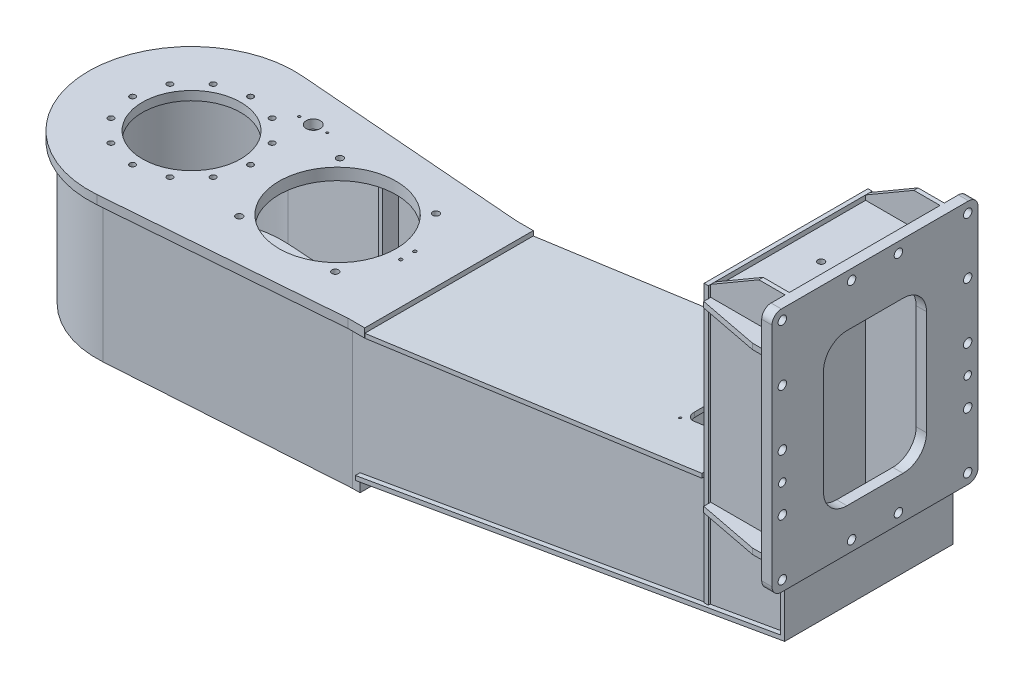
SolidWorks part; units mm, degrees
ref_plane "正面" through (0, 0, 0) normal (0, 0, 1) x (1, 0, 0)
ref_plane "平面" through (0, 0, 0) normal (0, 1, 0) x (1, 0, 0)
ref_plane "右側面" through (0, 0, 0) normal (1, 0, 0) x (0, 0, -1)
sketch "ｽｹｯﾁ1" plane through (0, 0, 0) normal (0, 1, 0) x (1, 0, 0)
  circle A0 centre (0, 0) radius 203
  circle A1 centre (0, 0) radius 194
extrude "ﾎﾞｽ - 押し出し1" add sketch "ｽｹｯﾁ1" against normal blind 301
sketch "ｽｹｯﾁ2" plane through (0, 0, 0) normal (0, 1, 0) x (1, 0, 0)
  line L0 (0, 0) -> (16.2249, -249.4729)
  line L1 (16.2249, -249.4729) -> (300, -249.4729)
  line L2 (300, -249.4729) -> (300, 249.4729)
  line L3 (300, 249.4729) -> (16.2249, 249.4729)
  line L4 (16.2249, 249.4729) -> (0, 0)
extrude "ｶｯﾄ - 押し出し1" cut sketch "ｽｹｯﾁ2" against normal through all and the other way through all
ref_plane "平面1" through (0, -301, 0) normal (0, 1, 0) x (1, 0, 0)
sketch "ｽｹｯﾁ4" plane through (0, -301, 0) normal (0, 1, 0) x (1, 0, 0)
  circle A0 centre (0, 0) radius 194
extrude "ﾎﾞｽ - 押し出し2" add sketch "ｽｹｯﾁ4" along normal blind 20
sketch "ｽｹｯﾁ5" plane through (0, -301, 0) normal (0, 1, 0) x (1, 0, 0)
  line L0 (12.5905, -193.591) -> (513.7, -161)
  line L1 (513.7, -161) -> (518, -161)
  line L2 (518, -161) -> (518, 161)
  line L3 (518, 161) -> (513.7, 161)
  line L4 (513.7, 161) -> (12.5905, 193.591)
  line L5 (12.5905, 193.591) -> (12.5905, -193.591)
extrude "ﾎﾞｽ - 押し出し3" add sketch "ｽｹｯﾁ5" along normal blind 20
sketch "ｽｹｯﾁ6" plane through (0, -301, 0) normal (0, 1, 0) x (1, 0, 0)
  circle A0 centre (0, 0) radius 159
sketch "ｽｹｯﾁ7" plane through (0, -301, 0) normal (0, 1, 0) x (1, 0, 0)
  circle A0 centre (0, 0) radius 159
extrude "ｶｯﾄ - 押し出し3" cut sketch "ｽｹｯﾁ7" along normal blind 20
sketch "ｽｹｯﾁ8" plane through (0, -301, 0) normal (0, 1, 0) x (1, 0, 0)
  line L0 (10.319, -158.6648) -> (468.0175, -128.8976)
  line L1 (468.0175, -128.8976) -> (468.0175, 128.8976)
  line L2 (468.0175, 128.8976) -> (10.319, 158.6648)
  line L3 (10.319, 158.6648) -> (10.319, -158.6648)
sketch "ｽｹｯﾁ9" plane through (0, -301, 0) normal (0, 1, 0) x (1, 0, 0)
  line L0 (10.319, -158.6648) -> (468.0175, -128.8976)
  line L1 (468.0175, -128.8976) -> (468.0175, 128.8976)
  line L2 (468.0175, 128.8976) -> (10.319, 158.6648)
  line L3 (10.319, 158.6648) -> (10.319, -158.6648)
extrude "ｶｯﾄ - 押し出し5" cut sketch "ｽｹｯﾁ9" along normal blind 20
fillet "ﾌｨﾚｯﾄ1" radius 25 2 edges at (468.0175, -291, -128.8976) (468.0175, -291, 128.8976)
sketch "ｽｹｯﾁ10" plane through (0, 0, 0) normal (0, 1, 0) x (1, 0, 0)
  line L0 (12.5905, 193.591) -> (513.7, 161)
  line L1 (513.7, 161) -> (530, 161)
  line L2 (530, 161) -> (530, 170)
  line L3 (530, 170) -> (514, 170)
  line L4 (514, 170) -> (13.1746, 202.572)
  line L5 (13.1746, 202.572) -> (12.5905, 193.591)
  line L6 (12.5905, -193.591) -> (513.7, -161)
  line L7 (513.7, -161) -> (530, -161)
  line L8 (530, -161) -> (530, -170)
  line L9 (530, -170) -> (514, -170)
  line L10 (514, -170) -> (13.1746, -202.572)
  line L11 (13.1746, -202.572) -> (12.5905, -193.591)
extrude "ﾎﾞｽ - 押し出し4" add sketch "ｽｹｯﾁ10" against normal blind 301
sketch "ｽｹｯﾁ11" plane through (0, 0, 0) normal (0, 1, 0) x (1, 0, 0)
  circle A0 centre (0, 0) radius 220
extrude "ﾎﾞｽ - 押し出し5" add sketch "ｽｹｯﾁ11" along normal blind 19
sketch "ｽｹｯﾁ12" plane through (0, 0, 0) normal (0, 1, 0) x (1, 0, 0)
  line L0 (17.3506, -219.3147) -> (514.3, -180)
  line L1 (514.3, -180) -> (550, -180)
  line L2 (550, -180) -> (550, 180)
  line L3 (550, 180) -> (514.3, 180)
  line L4 (514.3, 180) -> (17.3506, 219.3147)
  line L5 (17.3506, 219.3147) -> (17.3506, -219.3147)
extrude "ﾎﾞｽ - 押し出し6" add sketch "ｽｹｯﾁ12" along normal blind 19
sketch "ｽｹｯﾁ13" plane through (0, 0, 0) normal (0, 1, 0) x (1, 0, 0)
  line L0 (175, 135) -> (475, 135)
  line L1 (475, 135) -> (475, -135)
  line L2 (475, -135) -> (175, -135)
  line L3 (175, -135) -> (175, 135)
extrude "ﾎﾞｽ - 押し出し7" add sketch "ｽｹｯﾁ13" against normal blind 6
ref_plane "平面2" through (518, 0, 0) normal (1, 0, 0) x (0, 0, -1)
sketch "ｽｹｯﾁ15" plane through (518, 0, 0) normal (1, 0, 0) x (0, 0, -1)
  line L0 (161, -301) -> (-161, -301)
  line L1 (-161, -301) -> (-161, -7)
  line L2 (-161, -7) -> (-151, 3)
  line L3 (-151, 3) -> (151, 3)
  line L4 (151, 3) -> (161, -7)
  line L5 (161, -7) -> (161, -301)
extrude "ﾎﾞｽ - 押し出し8" add sketch "ｽｹｯﾁ15" along normal blind 12
sketch "ｽｹｯﾁ16" plane through (518, 0, 0) normal (1, 0, 0) x (0, 0, -1)
  line L0 (-111, -220) -> (-111, -97)
  line L1 (-81, -67) -> (81, -67)
  line L2 (111, -97) -> (111, -220)
  line L3 (81, -250) -> (-81, -250)
  arc A0 (-111, -97) -> (-81, -67) centre (-81, -97) cw
  arc A1 (81, -67) -> (111, -97) centre (81, -97) cw
  arc A2 (111, -220) -> (81, -250) centre (81, -220) cw
  arc A3 (-81, -250) -> (-111, -220) centre (-81, -220) cw
sketch "ｽｹｯﾁ17" plane through (518, 0, 0) normal (1, 0, 0) x (0, 0, -1)
  line L0 (-111, -220) -> (-111, -97)
  line L1 (-81, -67) -> (81, -67)
  line L2 (111, -97) -> (111, -220)
  line L3 (81, -250) -> (-81, -250)
  arc A0 (-111, -97) -> (-81, -67) centre (-81, -97) cw
  arc A1 (81, -67) -> (111, -97) centre (81, -97) cw
  arc A2 (111, -220) -> (81, -250) centre (81, -220) cw
  arc A3 (-81, -250) -> (-111, -220) centre (-81, -220) cw
extrude "ｶｯﾄ - 押し出し7" cut sketch "ｽｹｯﾁ17" along normal blind 12
ref_plane "平面3" through (0, 0, 161) normal (0, 0, 1) x (1, 0, 0)
ref_plane "平面4" through (0, 0, -161) normal (0, 0, 1) x (1, 0, 0)
sketch "ｽｹｯﾁ20" plane through (0, 0, 161) normal (0, 0, 1) x (1, 0, 0)
  line L0 (530, -273.1369) -> (1270, -143.5554)
  line L1 (1270, -143.5554) -> (1270, 109.9881)
  line L2 (1270, 109.9881) -> (530, 6.2151)
  line L3 (530, 6.2151) -> (530, -273.1369)
extrude "ﾎﾞｽ - 押し出し9" add sketch "ｽｹｯﾁ20" along normal blind 9
sketch "ｽｹｯﾁ21" plane through (0, 0, -161) normal (0, 0, 1) x (1, 0, 0)
  line L0 (530, -273.1369) -> (1270, -143.5554)
  line L1 (1270, -143.5554) -> (1270, 109.9881)
  line L2 (1270, 109.9881) -> (530, 6.2151)
  line L3 (530, 6.2151) -> (530, -273.1369)
extrude "ﾎﾞｽ - 押し出し10" add sketch "ｽｹｯﾁ21" against normal blind 9
sketch "ｽｹｯﾁ22" plane through (0, 0, 0) normal (0, 0, 1) x (1, 0, 0)
  line L0 (551.2, 0.1) -> (1270, 100.9)
  line L1 (1270, 100.9) -> (1270, 109.9881)
  line L2 (1270, 109.9881) -> (549.9501, 9.0128)
  line L3 (549.9501, 9.0128) -> (551.2, 0.1)
extrude "ﾎﾞｽ - 押し出し11" add sketch "ｽｹｯﾁ22" against normal blind 180 and the other way blind 180
sketch "ｽｹｯﾁ23" plane through (0, 0, 0) normal (0, 0, 1) x (1, 0, 0)
  line L0 (530, -264) -> (1438, -105)
  line L1 (1438, -105) -> (1438, -5)
  line L2 (1438, -5) -> (1447, -5)
  line L3 (1447, -5) -> (1447, -112.561)
  line L4 (1447, -112.561) -> (530, -273.1369)
  line L5 (530, -273.1369) -> (530, -264)
extrude "ﾎﾞｽ - 押し出し12" add sketch "ｽｹｯﾁ23" against normal blind 180 and the other way blind 180
sketch "ｽｹｯﾁ24" plane through (0, 0, 0) normal (0, 0, 1) x (1, 0, 0)
  line L0 (909.0501, 59.3707) -> (917.9629, 60.6206)
  line L1 (917.9629, 60.6206) -> (954.3466, -198.8296)
  line L2 (954.3466, -198.8296) -> (945.4763, -200.3828)
  line L3 (945.4763, -200.3828) -> (909.0501, 59.3707)
extrude "ﾎﾞｽ - 押し出し13" add sketch "ｽｹｯﾁ24" against normal blind 161 and the other way blind 161
ref_plane "平面5" through (0, 0, 161) normal (0, 0, 1) x (1, 0, 0)
ref_plane "平面6" through (0, 0, -161) normal (0, 0, 1) x (1, 0, 0)
sketch "ｽｹｯﾁ29" plane through (908.596, 127.4158, 0) normal (0.9903, 0.1389, 0) x (0, 0, -1)
  line L0 (81, -270.0172) -> (-81, -270.0172)
  line L1 (-111, -240.0172) -> (-111, -157.0172)
  line L2 (-81, -127.0172) -> (81, -127.0172)
  line L3 (111, -157.0172) -> (111, -240.0172)
  arc A0 (-81, -270.0172) -> (-111, -240.0172) centre (-81, -240.0172) cw
  arc A1 (-111, -157.0172) -> (-81, -127.0172) centre (-81, -157.0172) cw
  arc A2 (81, -127.0172) -> (111, -157.0172) centre (81, -157.0172) cw
  arc A3 (111, -240.0172) -> (81, -270.0172) centre (81, -240.0172) cw
extrude "ｶｯﾄ - 押し出し8" cut sketch "ｽｹｯﾁ29" against normal blind 9
ref_plane "平面7" through (1270, 0, 0) normal (1, 0, 0) x (0, 0, -1)
sketch "ｽｹｯﾁ31" plane through (1270, 0, 0) normal (1, 0, 0) x (0, 0, -1)
  line L0 (175, -132) -> (-175, -132)
  line L1 (-175, -132) -> (-175, 459)
  line L2 (-175, 459) -> (175, 459)
  line L3 (175, 459) -> (175, -132)
extrude "ﾎﾞｽ - 押し出し14" add sketch "ｽｹｯﾁ31" along normal blind 9
sketch "ｽｹｯﾁ32" plane through (0, 0, 161) normal (0, 0, 1) x (1, 0, 0)
  line L0 (1279, -5) -> (1438, -5)
  line L1 (1438, -5) -> (1438, 519)
  line L2 (1438, 519) -> (1382, 519)
  line L3 (1382, 519) -> (1279, 459)
  line L4 (1279, 459) -> (1279, -5)
ref_plane "平面8" through (0, 0, 161) normal (0, 0, 1) x (1, 0, 0)
ref_plane "平面9" through (0, 0, -161) normal (0, 0, 1) x (1, 0, 0)
ref_plane "平面10" through (1270, 0, 0) normal (1, 0, 0) x (0, 0, -1)
sketch "ｽｹｯﾁ36" plane through (0, 0, 161) normal (0, 0, 1) x (1, 0, 0)
  line L0 (1279, -5) -> (1460, -5)
  line L1 (1460, -5) -> (1460, 519)
  line L2 (1460, 519) -> (1382, 519)
  line L3 (1382, 519) -> (1279, 459)
  line L4 (1279, 459) -> (1279, -5)
extrude "ﾎﾞｽ - 押し出し16" add sketch "ｽｹｯﾁ36" along normal blind 9
sketch "ｽｹｯﾁ37" plane through (0, 0, -161) normal (0, 0, 1) x (1, 0, 0)
  line L0 (1279, -5) -> (1460, -5)
  line L1 (1460, -5) -> (1460, 519)
  line L2 (1460, 519) -> (1382, 519)
  line L3 (1382, 519) -> (1279, 459)
  line L4 (1279, 459) -> (1279, -5)
extrude "ﾎﾞｽ - 押し出し17" add sketch "ｽｹｯﾁ37" against normal blind 9
ref_plane "平面11" through (0, 44, 0) normal (0, 1, 0) x (1, 0, 0)
sketch "ｽｹｯﾁ39" plane through (0, 44, 0) normal (0, 1, 0) x (1, 0, 0)
  line L0 (1279, 170) -> (1431, 170)
  line L1 (1431, 170) -> (1438, 177)
  line L2 (1438, 177) -> (1438, 203)
  line L3 (1438, 203) -> (1431, 210)
  line L4 (1431, 210) -> (1408, 210)
  line L5 (1408, 210) -> (1279, 185)
  line L6 (1279, 185) -> (1279, 170)
  line L7 (1279, -170) -> (1431, -170)
  line L8 (1431, -170) -> (1438, -177)
  line L9 (1438, -177) -> (1438, -203)
  line L10 (1438, -203) -> (1431, -210)
  line L11 (1431, -210) -> (1408, -210)
  line L12 (1408, -210) -> (1279, -185)
  line L13 (1279, -185) -> (1279, -170)
extrude "ﾎﾞｽ - 押し出し18" add sketch "ｽｹｯﾁ39" along normal blind 12
ref_plane "平面12" through (0, 423, 0) normal (0, 1, 0) x (1, 0, 0)
sketch "ｽｹｯﾁ41" plane through (0, 423, 0) normal (0, 1, 0) x (1, 0, 0)
  line L0 (1279, 170) -> (1431, 170)
  line L1 (1431, 170) -> (1438, 177)
  line L2 (1438, 177) -> (1438, 203)
  line L3 (1438, 203) -> (1431, 210)
  line L4 (1431, 210) -> (1408, 210)
  line L5 (1408, 210) -> (1279, 185)
  line L6 (1279, 185) -> (1279, 170)
  line L7 (1279, -170) -> (1431, -170)
  line L8 (1431, -170) -> (1438, -177)
  line L9 (1438, -177) -> (1438, -203)
  line L10 (1438, -203) -> (1431, -210)
  line L11 (1431, -210) -> (1408, -210)
  line L12 (1408, -210) -> (1279, -185)
  line L13 (1279, -185) -> (1279, -170)
extrude "ﾎﾞｽ - 押し出し19" add sketch "ｽｹｯﾁ41" along normal blind 12
ref_plane "平面13" through (0, 437, 0) normal (0, 1, 0) x (1, 0, 0)
sketch "ｽｹｯﾁ43" plane through (0, 437, 0) normal (0, 1, 0) x (1, 0, 0)
  line L0 (1279, 161) -> (1438, 161)
  line L1 (1438, 161) -> (1438, -161)
  line L2 (1438, -161) -> (1279, -161)
  line L3 (1279, -161) -> (1279, 161)
extrude "ﾎﾞｽ - 押し出し20" add sketch "ｽｹｯﾁ43" along normal blind 12
ref_plane "平面14" through (1438, 0, 0) normal (1, 0, 0) x (0, 0, -1)
sketch "ｽｹｯﾁ45" plane through (1438, 0, 0) normal (1, 0, 0) x (0, 0, -1)
  line L0 (-220, 15) -> (-220, 499)
  line L1 (-200, 519) -> (200, 519)
  line L2 (220, 499) -> (220, 15)
  line L3 (200, -5) -> (-200, -5)
  arc A0 (-220, 499) -> (-200, 519) centre (-200, 499) cw
  arc A1 (200, 519) -> (220, 499) centre (200, 499) cw
  arc A2 (220, 15) -> (200, -5) centre (200, 15) cw
  arc A3 (-200, -5) -> (-220, 15) centre (-200, 15) cw
extrude "ﾎﾞｽ - 押し出し21" add sketch "ｽｹｯﾁ45" along normal blind 22
sketch "ｽｹｯﾁ46" plane through (1438, 0, 0) normal (1, 0, 0) x (0, 0, -1)
  line L0 (-110, 135) -> (-110, 359)
  line L1 (-60, 409) -> (60, 409)
  line L2 (110, 359) -> (110, 135)
  line L3 (60, 85) -> (-60, 85)
  arc A0 (-110, 359) -> (-60, 409) centre (-60, 359) cw
  arc A1 (60, 409) -> (110, 359) centre (60, 359) cw
  arc A2 (110, 135) -> (60, 85) centre (60, 135) cw
  arc A3 (-60, 85) -> (-110, 135) centre (-60, 135) cw
sketch "ｽｹｯﾁ47" plane through (1438, 0, 0) normal (1, 0, 0) x (0, 0, -1)
  line L0 (-110, 135) -> (-110, 359)
  line L1 (-60, 409) -> (60, 409)
  line L2 (110, 359) -> (110, 135)
  line L3 (60, 85) -> (-60, 85)
  arc A0 (-110, 359) -> (-60, 409) centre (-60, 359) cw
  arc A1 (60, 409) -> (110, 359) centre (60, 359) cw
  arc A2 (110, 135) -> (60, 85) centre (60, 135) cw
  arc A3 (-60, 85) -> (-110, 135) centre (-60, 135) cw
extrude "ｶｯﾄ - 押し出し10" cut sketch "ｽｹｯﾁ47" along normal blind 22
sketch "ｽｹｯﾁ48" plane through (0, 0, 0) normal (0, 1, 0) x (1, 0, 0)
  line L0 (253.6175, 145.9656) -> (262.6175, 145.3656)
  line L1 (262.6175, 145.3656) -> (264.7175, 177.1935)
  line L2 (264.7175, 177.1935) -> (255.7175, 177.7788)
  line L3 (255.7175, 177.7788) -> (253.6175, 145.9656)
  line L4 (253.6175, -145.9656) -> (262.6175, -145.3656)
  line L5 (262.6175, -145.3656) -> (264.7175, -177.1935)
  line L6 (264.7175, -177.1935) -> (255.7175, -177.7788)
  line L7 (255.7175, -177.7788) -> (253.6175, -145.9656)
extrude "ﾎﾞｽ - 押し出し22" add sketch "ｽｹｯﾁ48" against normal blind 301
sketch "ｽｹｯﾁ49" plane through (0, 0, 0) normal (0, 1, 0) x (1, 0, 0)
  circle A0 centre (0, 0) radius 105
sketch "ｽｹｯﾁ50" plane through (0, 0, 0) normal (0, 1, 0) x (1, 0, 0)
  circle A0 centre (0, 0) radius 105
extrude "ｶｯﾄ - 押し出し12" cut sketch "ｽｹｯﾁ50" along normal blind 19
sketch "ｽｹｯﾁ51" plane through (0, 0, 0) normal (0, 1, 0) x (1, 0, 0)
  circle A0 centre (126, 0) radius 6
  circle A1 centre (109.1192, -63) radius 6
  circle A2 centre (63, -109.1192) radius 6
  circle A3 centre (0, -126) radius 6
  circle A4 centre (-63, -109.1192) radius 6
  circle A5 centre (-109.1192, -63) radius 6
  circle A6 centre (-126, 0) radius 6
  circle A7 centre (-109.1192, 63) radius 6
  circle A8 centre (-63, 109.1192) radius 6
  circle A9 centre (0, 126) radius 6
  circle A10 centre (63, 109.1192) radius 6
  circle A11 centre (109.1192, 63) radius 6
sketch "ｽｹｯﾁ52" plane through (0, 0, 0) normal (0, 1, 0) x (1, 0, 0)
  circle A0 centre (126, 0) radius 6
  circle A1 centre (109.1192, -63) radius 6
  circle A2 centre (63, -109.1192) radius 6
  circle A3 centre (0, -126) radius 6
  circle A4 centre (-63, -109.1192) radius 6
  circle A5 centre (-109.1192, -63) radius 6
  circle A6 centre (-126, 0) radius 6
  circle A7 centre (-109.1192, 63) radius 6
  circle A8 centre (-63, 109.1192) radius 6
  circle A9 centre (0, 126) radius 6
  circle A10 centre (63, 109.1192) radius 6
  circle A11 centre (109.1192, 63) radius 6
extrude "ｶｯﾄ - 押し出し14" cut sketch "ｽｹｯﾁ52" along normal blind 19
sketch "ｽｹｯﾁ53" plane through (0, 0, 0) normal (0, 1, 0) x (1, 0, 0)
  circle A0 centre (119, 141) radius 15
sketch "ｽｹｯﾁ54" plane through (0, 0, 0) normal (0, 1, 0) x (1, 0, 0)
  circle A0 centre (119, 141) radius 15
extrude "ｶｯﾄ - 押し出し16" cut sketch "ｽｹｯﾁ54" along normal blind 19
sketch "ｽｹｯﾁ55" plane through (0, 0, 0) normal (0, 1, 0) x (1, 0, 0)
  circle A0 centre (89, 141) radius 2.5
  circle A1 centre (149, 141) radius 2.5
sketch "ｽｹｯﾁ56" plane through (0, 0, 0) normal (0, 1, 0) x (1, 0, 0)
  circle A0 centre (89, 141) radius 2.5
  circle A1 centre (149, 141) radius 2.5
extrude "ｶｯﾄ - 押し出し18" cut sketch "ｽｹｯﾁ56" along normal blind 19
ref_plane "平面15" through (0, -6, 0) normal (0, 1, 0) x (1, 0, 0)
sketch "ｽｹｯﾁ58" plane through (0, -6, 0) normal (0, 1, 0) x (1, 0, 0)
  circle A0 centre (312, 0) radius 125
sketch "ｽｹｯﾁ59" plane through (0, -6, 0) normal (0, 1, 0) x (1, 0, 0)
  circle A0 centre (312, 0) radius 125
extrude "ｶｯﾄ - 押し出し20" cut sketch "ｽｹｯﾁ59" along normal blind 25
sketch "ｽｹｯﾁ60" plane through (0, -6, 0) normal (0, 1, 0) x (1, 0, 0)
  circle A0 centre (209.5, 107.5) radius 7
  circle A1 centre (209.5, -107.5) radius 7
  circle A2 centre (414.5, 107.5) radius 7
  circle A3 centre (414.5, -107.5) radius 7
sketch "ｽｹｯﾁ61" plane through (0, -6, 0) normal (0, 1, 0) x (1, 0, 0)
  circle A0 centre (209.5, 107.5) radius 7
  circle A1 centre (209.5, -107.5) radius 7
  circle A2 centre (414.5, 107.5) radius 7
  circle A3 centre (414.5, -107.5) radius 7
extrude "ｶｯﾄ - 押し出し22" cut sketch "ｽｹｯﾁ61" along normal blind 25
sketch "ｽｹｯﾁ62" plane through (0, -6, 0) normal (0, 1, 0) x (1, 0, 0)
  circle A0 centre (462, 15) radius 3.4
  circle A1 centre (462, -15) radius 3.4
sketch "ｽｹｯﾁ63" plane through (0, -6, 0) normal (0, 1, 0) x (1, 0, 0)
  circle A0 centre (462, 15) radius 3.4
  circle A1 centre (462, -15) radius 3.4
extrude "ｶｯﾄ - 押し出し24" cut sketch "ｽｹｯﾁ63" along normal blind 25
sketch "ｽｹｯﾁ64" plane through (9.3669, -66.7952, 0) normal (-0.1389, 0.9903, 0) x (0.9903, 0.1389, 0)
  line L0 (1205.5769, 55) -> (1205.5769, -55)
  line L1 (1185.5769, -75) -> (1150.5769, -75)
  line L2 (1130.5769, -55) -> (1130.5769, 55)
  line L3 (1150.5769, 75) -> (1185.5769, 75)
  arc A0 (1205.5769, -55) -> (1185.5769, -75) centre (1185.5769, -55) cw
  arc A1 (1150.5769, -75) -> (1130.5769, -55) centre (1150.5769, -55) cw
  arc A2 (1130.5769, 55) -> (1150.5769, 75) centre (1150.5769, 55) cw
  arc A3 (1185.5769, 75) -> (1205.5769, 55) centre (1185.5769, 55) cw
extrude "ｶｯﾄ - 押し出し25" cut sketch "ｽｹｯﾁ64" against normal blind 9
sketch "ｽｹｯﾁ65" plane through (9.3669, -66.7952, 0) normal (-0.1389, 0.9903, 0) x (0.9903, 0.1389, 0)
  circle A0 centre (1125.5769, 80) radius 2.5
  circle A1 centre (1125.5769, -80) radius 2.5
  circle A2 centre (1210.5769, 80) radius 2.5
  circle A3 centre (1210.5769, -80) radius 2.5
extrude "ｶｯﾄ - 押し出し26" cut sketch "ｽｹｯﾁ65" against normal blind 9
sketch "ｽｹｯﾁ66" plane through (1270, 0, 0) normal (1, 0, 0) x (0, 0, -1)
  circle A0 centre (0, 319) radius 65
sketch "ｽｹｯﾁ67" plane through (1270, 0, 0) normal (1, 0, 0) x (0, 0, -1)
  circle A0 centre (0, 319) radius 65
extrude "ｶｯﾄ - 押し出し28" cut sketch "ｽｹｯﾁ67" along normal blind 9
sketch "ｽｹｯﾁ68" plane through (1270, 0, 0) normal (1, 0, 0) x (0, 0, -1)
  circle A0 centre (-53.033, 372.033) radius 2.5
  circle A1 centre (53.033, 372.033) radius 2.5
  circle A2 centre (53.033, 265.967) radius 2.5
  circle A3 centre (-53.033, 265.967) radius 2.5
sketch "ｽｹｯﾁ69" plane through (1270, 0, 0) normal (1, 0, 0) x (0, 0, -1)
  circle A0 centre (-53.033, 372.033) radius 2.5
  circle A1 centre (53.033, 372.033) radius 2.5
  circle A2 centre (53.033, 265.967) radius 2.5
  circle A3 centre (-53.033, 265.967) radius 2.5
extrude "ｶｯﾄ - 押し出し30" cut sketch "ｽｹｯﾁ69" along normal blind 9
sketch "ｽｹｯﾁ70" plane through (0, 437, 0) normal (0, 1, 0) x (1, 0, 0)
  circle A0 centre (1345, 0) radius 7
sketch "ｽｹｯﾁ71" plane through (0, 437, 0) normal (0, 1, 0) x (1, 0, 0)
  circle A0 centre (1345, 0) radius 7
extrude "ｶｯﾄ - 押し出し32" cut sketch "ｽｹｯﾁ71" along normal blind 12
sketch "ｽｹｯﾁ72" plane through (1438, 0, 0) normal (1, 0, 0) x (0, 0, -1)
  circle A0 centre (198, 17) radius 9
  circle A1 centre (198, 137) radius 9
  circle A2 centre (198, 257) radius 9
  circle A3 centre (198, 377) radius 9
  circle A4 centre (198, 497) radius 9
  circle A5 centre (-198, 17) radius 9
  circle A6 centre (-198, 137) radius 9
  circle A7 centre (-198, 257) radius 9
  circle A8 centre (-198, 377) radius 9
  circle A9 centre (-198, 497) radius 9
  circle A10 centre (50, 17) radius 9
  circle A11 centre (50, 497) radius 9
  circle A12 centre (-50, 17) radius 9
  circle A13 centre (-50, 497) radius 9
sketch "ｽｹｯﾁ73" plane through (1438, 0, 0) normal (1, 0, 0) x (0, 0, -1)
  circle A0 centre (198, 17) radius 9
  circle A1 centre (198, 137) radius 9
  circle A2 centre (198, 257) radius 9
  circle A3 centre (198, 377) radius 9
  circle A4 centre (198, 497) radius 9
  circle A5 centre (-198, 17) radius 9
  circle A6 centre (-198, 137) radius 9
  circle A7 centre (-198, 257) radius 9
  circle A8 centre (-198, 377) radius 9
  circle A9 centre (-198, 497) radius 9
  circle A10 centre (50, 17) radius 9
  circle A11 centre (50, 497) radius 9
  circle A12 centre (-50, 17) radius 9
  circle A13 centre (-50, 497) radius 9
extrude "ｶｯﾄ - 押し出し34" cut sketch "ｽｹｯﾁ73" along normal blind 22
sketch "ｽｹｯﾁ74" plane through (1438, 0, 0) normal (1, 0, 0) x (0, 0, -1)
  circle A0 centre (198, 197) radius 8
  circle A1 centre (-198, 197) radius 8
sketch "ｽｹｯﾁ75" plane through (1438, 0, 0) normal (1, 0, 0) x (0, 0, -1)
  circle A0 centre (198, 197) radius 8
  circle A1 centre (-198, 197) radius 8
extrude "ｶｯﾄ - 押し出し36" cut sketch "ｽｹｯﾁ75" along normal blind 22
ref_plane "平面16" through (0, 0, 161) normal (0, 0, 1) x (1, 0, 0)
ref_plane "平面17" through (0, 0, -161) normal (0, 0, 1) x (1, 0, 0)
sketch "ｽｹｯﾁ78" plane through (0, 0, 161) normal (0, 0, 1) x (1, 0, 0)
  line L0 (1279, -136.8425) -> (1444, -107.9493)
  line L1 (1444, -107.9493) -> (1444, 300)
  line L2 (1444, 300) -> (1279, 300)
  line L3 (1279, 300) -> (1279, -136.8425)
extrude "ﾎﾞｽ - 押し出し23" add sketch "ｽｹｯﾁ78" along normal blind 9
sketch "ｽｹｯﾁ79" plane through (0, 0, -161) normal (0, 0, 1) x (1, 0, 0)
  line L0 (1279, -136.8425) -> (1444, -107.9493)
  line L1 (1444, -107.9493) -> (1444, 300)
  line L2 (1444, 300) -> (1279, 300)
  line L3 (1279, 300) -> (1279, -136.8425)
extrude "ﾎﾞｽ - 押し出し24" add sketch "ｽｹｯﾁ79" against normal blind 9
